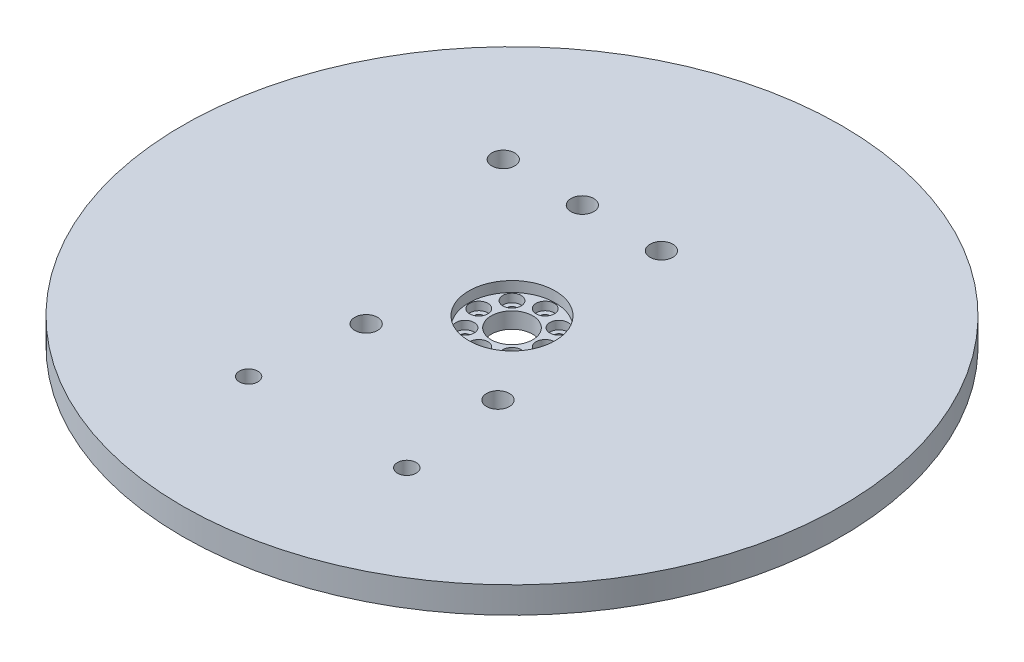
SolidWorks part; units mm, degrees
other "Markup1"
sketch "Sketch21" plane through (-65.5, -15.05, -60) normal (-0.0927, -0.2854, -0.9539) x (0.9951, -0.0609, -0.0785)
material "6061 Alloy"
ref_plane "Front Plane" through (0, 0, 0) normal (0, 0, 1) x (1, 0, 0)
ref_plane "Top Plane" through (0, 0, 0) normal (0, 1, 0) x (1, 0, 0)
ref_plane "Right Plane" through (0, 0, 0) normal (1, 0, 0) x (0, 0, -1)
sketch "Sketch1" plane through (0, 0, 0) normal (0, 1, 0) x (1, 0, 0)
  circle A0 centre (0, 0) radius 79.375
  dimension "D1" = 158.75
extrude "Boss-Extrude1" add sketch "Sketch1" along normal mid plane 6.35
sketch "Sketch2" plane through (0, -3.175, 0) normal (0, -1, 0) x (1, 0, 0)
  circle A0 centre (0, 0) radius 12.065
  circle A1 centre (0, 0) radius 79.375 construction
  dimension "D1" = 24.13
sketch "Sketch5" plane through (0, 3.175, 0) normal (0, 1, 0) x (1, 0, 0)
  circle A0 centre (0, 0) radius 10.4
  circle A1 centre (0, 0) radius 79.375 construction
  dimension "D1" = 20.8
extrude "Cut-Extrude1" cut sketch "Sketch5" against normal offset from surface (2.5 mm away) 2.5 up to face at (0, 3.175, 79.375)
sketch "Sketch6" plane through (0, 3.175, 0) normal (0, 1, 0) x (1, 0, 0)
  circle A0 centre (0, 0) radius 5
  circle A1 centre (0, 0) radius 10.4 construction
  dimension "D1" = 10
extrude "Cut-Extrude2" cut sketch "Sketch6" against normal through all
sketch "Sketch15" plane through (0, -3.175, 0) normal (0, 1, 0) x (1, 0, 0)
  circle A0 centre (0, 8) radius 1
  circle A1 centre (-5.6569, 5.6569) radius 1
  circle A2 centre (5.6569, 5.6569) radius 1
  circle A3 centre (-5.6569, -5.6569) radius 1
  circle A4 centre (5.6569, -5.6569) radius 1
  circle A5 centre (-8, 0) radius 1
  circle A6 centre (0, -8) radius 1
  circle A7 centre (8, 0) radius 1
  circle A8 centre (0, 0) radius 4
  circle A9 centre (0, 0) radius 11
  circle A10 centre (0, 0) radius 2.25
  circle A11 centre (0, 0) radius 5
  circle A12 centre (0, 0) radius 5 construction
  dimension "D1" = 4.5
  dimension "D2" = 8
  dimension "D3" = 10
  dimension "D4" = 22
  dimension "D5" = 2
  dimension "D6" = 8
  dimension "D7" = 5.6569
  dimension "D8" = 8
  dimension "D9" = 5.6569
  dimension "D10" = 5.6569
  dimension "D11" = 8
  dimension "D12" = 5.6569
  dimension "D13" = 8
hole_wizard "CBORE for M2 SHCS1" positions "Sketch19" profile "Sketch20" counterbore size "M2" standard "ANSI Metric"
sketch "Sketch19" plane through (0, 0.675, 0) normal (0, 1, 0) x (1, 0, 0)
  point P0 (-5.6569, 5.6569)
  point P3 (0, 8)
  point P6 (5.6569, 5.6569)
  point P9 (8, 0)
  point P12 (5.6569, -5.6569)
  point P15 (0, -8)
  point P18 (-5.6569, -5.6569)
  point P21 (-8, 0)
sketch "Sketch20" plane through (-5.6569, 0.675, -5.6569) normal (1, 0, 0) x (0, 0, 1)
  line L0 (0, 0) -> (0, 6.6609)
  line L1 (0, 6.6609) -> (1.1, 6)
  line L2 (1.1, 6) -> (1.1, 2)
  line L3 (1.1, 2) -> (2.2, 2)
  line L4 (2.2, 2) -> (2.2, 0)
  line L5 (2.2, 0) -> (0, 0)
  line L10 (0, 6.6609) -> (-1.1, 6) construction
  line L11 (0, -6.35) -> (0, 107.95) construction
  dimension "Hole Dia." = 2.2
  dimension "Hole Depth" = 6
  dimension "C'Bore Dia." = 4.4
  dimension "C'Bore Depth" = 2
  dimension "Drill Angle" = 118
hole_wizard "M4 Clearance Hole1" positions "Sketch22" profile "Sketch23" hole size "M4" standard "ANSI Metric" end condition through all
sketch "Sketch22" plane through (0, 3.175, 0) normal (0, 1, 0) x (1, 0, 0)
  point P0 (19.05, -44.3882)
  point P3 (-19.05, -44.3882)
sketch "Sketch23" plane through (19.05, 3.175, 44.3882) normal (1, 0, 0) x (0, 0, 1)
  line L0 (0, 0) -> (0, 6.35)
  line L1 (0, 6.35) -> (2.25, 6.35)
  line L2 (2.25, 6.35) -> (2.25, 0)
  line L5 (2.25, 0) -> (0, 0)
  line L11 (0, -6.35) -> (0, 107.95) construction
  dimension "Thru Hole Dia." = 4.5
  dimension "Thru Hole Depth" = 6.35
hole_wizard "M5 Clearance Hole1" positions "Sketch24" profile "Sketch25" hole size "M5" standard "ANSI Metric" end condition through all
sketch "Sketch24" plane through (0, 3.175, 0) normal (0, 1, 0) x (1, 0, 0)
  point P0 (-33.6688, 31.5674)
  point P3 (-14.6188, 31.5674)
  point P6 (4.4312, 31.5674)
  point P9 (-15.875, -19.2497)
  point P12 (15.875, -19.2497)
sketch "Sketch25" plane through (-33.6688, 3.175, -31.5674) normal (1, 0, 0) x (0, 0, 1)
  line L0 (0, 0) -> (0, 6.35)
  line L1 (0, 6.35) -> (2.75, 6.35)
  line L2 (2.75, 6.35) -> (2.75, 0)
  line L5 (2.75, 0) -> (0, 0)
  line L11 (0, -6.35) -> (0, 107.95) construction
  dimension "Thru Hole Dia." = 5.5
  dimension "Thru Hole Depth" = 6.35
